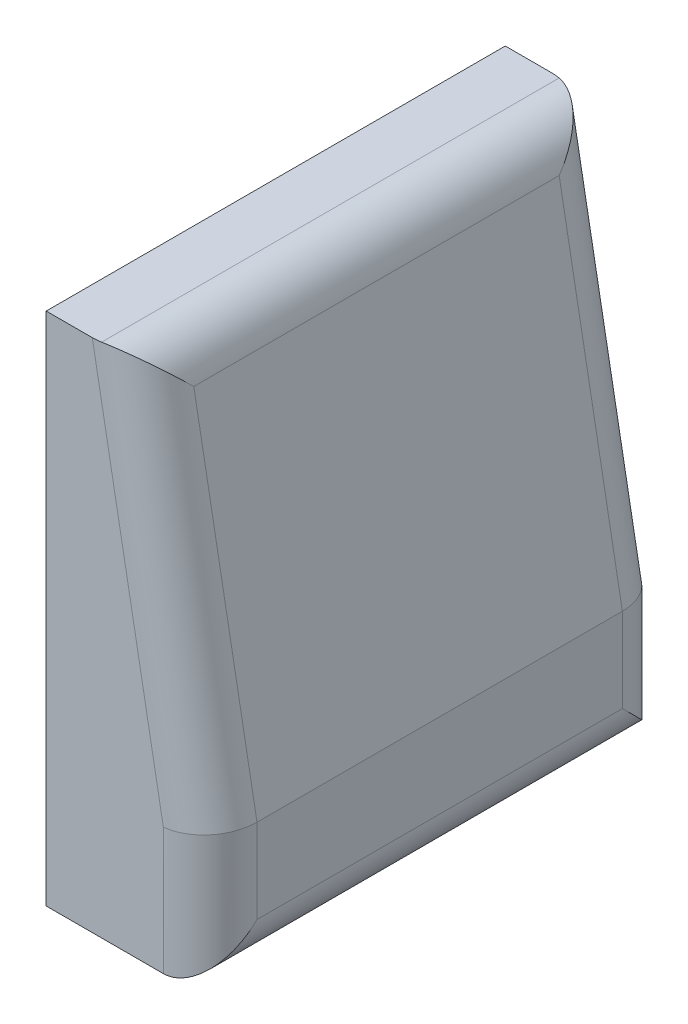
SolidWorks part; units mm, degrees
ref_plane "Front Plane" through (0, 0, 0) normal (0, 0, 1) x (1, 0, 0)
ref_plane "Top Plane" through (0, 0, 0) normal (0, 1, 0) x (1, 0, 0)
ref_plane "Right Plane" through (0, 0, 0) normal (1, 0, 0) x (0, 0, -1)
sketch "Sketch1" plane through (0, 0, 0) normal (0, 0, 1) x (1, 0, 0)
  line L0 (0, 550) -> (0, -550)
  line L1 (0, -550) -> (350, -550)
  line L2 (350, -550) -> (350, -270)
  line L3 (350, -270) -> (200, 550)
  line L4 (200, 550) -> (0, 550)
  dimension "D1" = 1100
  dimension "D2" = 200
  dimension "D3" = 350
  dimension "D4" = 280
extrude "Boss-Extrude1" add sketch "Sketch1" along normal mid plane 980
fillet "Fillet1" radius 100 6 edges at (350, -550, 0) (350, -410, 490) (350, -410, -490) (275, 140, -490) (275, 140, 490) (200, 550, 0)
